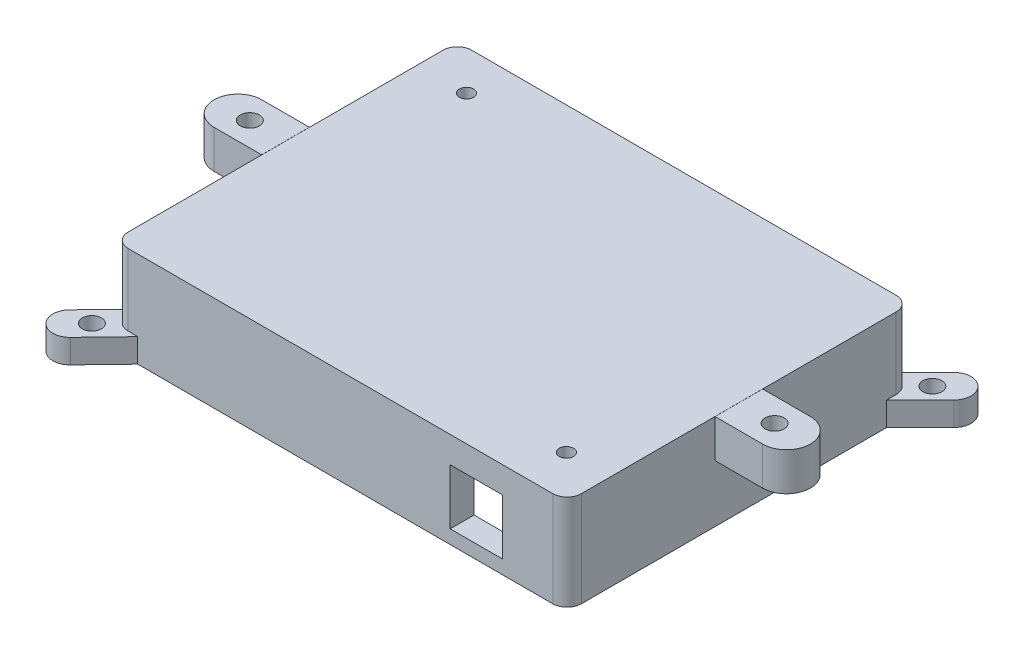
SolidWorks part; units mm, degrees
ref_plane "Plano frontal" through (0, 0, 0) normal (0, 0, 1) x (1, 0, 0)
ref_plane "Plano superior" through (0, 0, 0) normal (0, 1, 0) x (1, 0, 0)
ref_plane "Plano direito" through (0, 0, 0) normal (1, 0, 0) x (0, 0, -1)
sketch "Esboço1" plane through (0, 0, 0) normal (0, 1, 0) x (1, 0, 0)
  line L0 (9.0167, -15.2186) -> (9.0167, -20.2186) construction
  line L1 (-75.9833, 46.7814) -> (9.0167, 46.7814) construction
  line L2 (-75.9833, 46.7814) -> (-75.9833, -15.2186) construction
  line L3 (-75.9833, -15.2186) -> (9.0167, -15.2186) construction
  line L4 (9.0167, 46.7814) -> (9.0167, -15.2186) construction
  line L5 (-77.9833, 51.7814) -> (11.0167, 51.7814)
  line L6 (-80.9833, 48.7814) -> (-80.9833, -17.2186)
  line L7 (-77.9833, -20.2186) -> (11.0167, -20.2186)
  line L8 (14.0167, 48.7814) -> (14.0167, -17.2186)
  line L9 (9.0167, 46.7814) -> (9.0167, 51.7814) construction
  line L10 (-75.9833, -15.2186) -> (-80.9833, -15.2186) construction
  line L11 (9.0167, -15.2186) -> (14.0167, -15.2186) construction
  arc A0 (-80.9833, -17.2186) -> (-77.9833, -20.2186) centre (-77.9833, -17.2186) ccw
  arc A1 (11.0167, -20.2186) -> (14.0167, -17.2186) centre (11.0167, -17.2186) ccw
  arc A2 (11.0167, 51.7814) -> (14.0167, 48.7814) centre (11.0167, 48.7814) cw
  arc A3 (-77.9833, 51.7814) -> (-80.9833, 48.7814) centre (-77.9833, 48.7814) ccw
  point P14 (-80.9833, -20.2186)
  point P17 (14.0167, -20.2186)
  point P20 (14.0167, 51.7814)
  dimension "D6" = 3
  dimension "D1" = 85
  dimension "D2" = 62
  dimension "D3" = 72
  dimension "D4" = 5
  dimension "D5" = 95
extrude "Ressalto-extrusão2" add sketch "Esboço1" along normal blind 20
sketch "Esboço5" plane through (0, 20, 0) normal (0, 1, 0) x (1, 0, 0)
  line L0 (-80.1046, -19.34) -> (13.1381, 50.9027) construction
  line L1 (13.1381, -19.34) -> (-80.1046, 50.9027) construction
  line L2 (14.0167, -17.2186) -> (14.0167, -20.2186) construction
  line L3 (14.0167, -20.2186) -> (11.0167, -20.2186) construction
  line L4 (11.0167, -20.2186) -> (-77.9833, -20.2186) construction
  line L5 (-77.9833, -20.2186) -> (-80.9833, -20.2186) construction
  line L6 (-80.9833, -20.2186) -> (-80.9833, -17.2186) construction
  line L7 (-80.9833, -17.2186) -> (-80.9833, 48.7814) construction
  line L8 (-80.9833, 48.7814) -> (-80.9833, 51.7814) construction
  line L9 (-80.9833, 51.7814) -> (-77.9833, 51.7814) construction
  line L10 (-77.9833, 51.7814) -> (11.0167, 51.7814) construction
  line L11 (11.0167, 51.7814) -> (14.0167, 51.7814) construction
  line L12 (14.0167, 51.7814) -> (14.0167, 48.7814) construction
  line L13 (14.0167, 48.7814) -> (14.0167, -17.2186) construction
  line L14 (9.0167, 51.7814) -> (9.0167, -20.2186) construction
  line L15 (-75.9833, 51.7814) -> (-75.9833, -20.2186) construction
  line L16 (-80.9833, -15.2186) -> (14.0167, -15.2186) construction
  line L17 (-80.9833, 46.7814) -> (14.0167, 46.7814) construction
  line L18 (-75.9833, -15.2186) -> (-75.9833, 46.7814)
  line L19 (-75.9833, 46.7814) -> (9.0167, 46.7814)
  line L20 (9.0167, 46.7814) -> (9.0167, -15.2186)
  line L21 (9.0167, -15.2186) -> (-75.9833, -15.2186)
  arc A0 (-80.9833, -17.2186) -> (-77.9833, -20.2186) centre (-77.9833, -17.2186) ccw construction
  arc A1 (14.0167, 48.7814) -> (11.0167, 51.7814) centre (11.0167, 48.7814) ccw construction
  arc A2 (11.0167, -20.2186) -> (14.0167, -17.2186) centre (11.0167, -17.2186) ccw construction
  arc A3 (-77.9833, 51.7814) -> (-80.9833, 48.7814) centre (-77.9833, 48.7814) ccw construction
  dimension "D1" = 5
  dimension "D2" = 5
  dimension "D3" = 5
  dimension "D4" = 5
extrude "Corte-extrusão1" cut sketch "Esboço5" along normal blind 15 from surface at -20 starting at face at (-33.4833, 0, -15.7814)
sketch "Esboço6" plane through (0, 0, 20.2186) normal (0, 0, 1) x (1, 0, 0)
  line L0 (-77.9833, 0) -> (11.0167, 0) construction
  line L1 (0.5167, 2.86) -> (-10.4833, 2.86)
  line L2 (0.5167, 2.86) -> (0.5167, 14.49)
  line L3 (0.5167, 14.49) -> (-10.4833, 14.49)
  line L4 (-10.4833, 2.86) -> (-10.4833, 14.49)
  line L5 (11.0167, 20) -> (11.0167, 0) construction
  dimension "D1" = 11
  dimension "D2" = 11.63
  dimension "D3" = 2.86
  dimension "D4" = 10.5
extrude "Corte-extrusão2" cut sketch "Esboço6" against normal up to next
sketch "Esboço7" plane through (0, 20, 0) normal (0, 1, 0) x (1, 0, 0)
  line L0 (-33.4833, 51.7814) -> (-33.4833, -20.2186) construction
  line L1 (11.0167, 51.7814) -> (-77.9833, 51.7814) construction
  line L2 (-77.9833, -20.2186) -> (11.0167, -20.2186) construction
  line L3 (14.0167, 15.7814) -> (-80.9833, 15.7814) construction
  line L4 (14.0167, -17.2186) -> (14.0167, 48.7814) construction
  line L5 (-80.9833, 48.7814) -> (-80.9833, -17.2186) construction
  line L7 (-43.0633, 51.7814) -> (-23.9033, 51.7814)
  line L14 (-80.1046, 50.9027) -> (13.1381, -19.34) construction
  line L15 (-80.1046, -19.34) -> (13.1381, 50.9027) construction
  line L20 (-90.9833, 10.7814) -> (-90.9833, 20.7814) construction
  line L22 (29.0167, 15.7814) -> (14.0167, 15.7814) construction
  line L23 (-81.006, 52.1765) -> (14.0167, 52.1765) construction
  line L24 (-81.006, 52.1765) -> (-81.006, -19.8235) construction
  line L25 (-81.006, -19.8235) -> (14.0167, -19.8235) construction
  line L26 (14.0167, 52.1765) -> (14.0167, -19.8235) construction
  line L30 (-95.9833, 15.7814) -> (-80.9833, 15.7814) construction
  line L31 (-90.9833, 20.7814) -> (-81.006, 20.7814)
  line L32 (-90.9833, 10.7814) -> (-81.006, 10.7814)
  line L33 (-81.006, 10.7814) -> (-81.006, 20.7814)
  line L34 (24.0167, 10.7814) -> (24.0167, 20.7814) construction
  line L38 (14.0395, 10.7814) -> (14.0395, 20.7814)
  line L39 (24.0167, 10.7814) -> (14.0395, 10.7814)
  line L40 (24.0167, 20.7814) -> (14.0395, 20.7814)
  arc A4 (-77.9833, 51.7814) -> (-80.9833, 48.7814) centre (-77.9833, 48.7814) ccw construction
  arc A5 (11.0167, -20.2186) -> (14.0167, -17.2186) centre (11.0167, -17.2186) ccw construction
  arc A6 (-80.9833, -17.2186) -> (-77.9833, -20.2186) centre (-77.9833, -17.2186) ccw construction
  arc A7 (14.0167, 48.7814) -> (11.0167, 51.7814) centre (11.0167, 48.7814) ccw construction
  arc A10 (-90.9833, 10.7814) -> (-90.9833, 20.7814) centre (-90.9833, 15.7814) cw
  circle A16 centre (-88.4833, 15.7814) radius 2
  circle A17 centre (21.5167, 15.7814) radius 2
  arc A18 (24.0167, 10.7814) -> (24.0167, 20.7814) centre (24.0167, 15.7814) ccw
  dimension "D4" = 10
  dimension "D1" = 15
  dimension "D2" = 7.5
sketch "Esboço8" plane through (0, 0, 0) normal (0, -1, 0) x (1, 0, 0)
  line L0 (9.0167, -51.7814) -> (14.0167, -46.7814)
  line L1 (11.5167, -49.2814) -> (21.0878, -58.8524) construction
  line L2 (-75.9833, -46.7814) -> (9.0167, 15.2186) construction
  line L3 (9.0167, -46.7814) -> (9.0167, -51.7814) construction
  line L4 (11.0167, -51.7814) -> (-77.9833, -51.7814) construction
  line L5 (-33.4833, 15.2186) -> (-33.4833, -46.7814) construction
  line L6 (-75.9833, 15.2186) -> (9.0167, 15.2186) construction
  line L7 (9.0167, -51.7814) -> (16.0878, -58.8524)
  line L8 (21.0878, -53.8524) -> (16.0878, -58.8524) construction
  line L9 (9.0167, -46.7814) -> (14.0167, -46.7814) construction
  line L10 (14.0167, 17.2186) -> (14.0167, -48.7814) construction
  line L11 (14.0167, -46.7814) -> (21.0878, -53.8524)
  line L12 (9.0167, -46.7814) -> (-75.9833, -46.7814) construction
  line L13 (-75.9833, -15.7814) -> (9.0167, -15.7814) construction
  line L14 (-75.9833, -46.7814) -> (-75.9833, 15.2186) construction
  line L15 (9.0167, 15.2186) -> (9.0167, -46.7814) construction
  line L23 (-75.9833, 20.2186) -> (-81.0747, 15.3135)
  line L24 (-78.4833, 17.7186) -> (-87.9197, 27.5133) construction
  line L25 (-75.9833, 15.2186) -> (-75.9833, 20.2186) construction
  line L26 (-88.0128, 22.5151) -> (-82.9214, 27.4202) construction
  line L27 (-75.9833, 15.2186) -> (-81.0747, 15.3135) construction
  line L28 (-75.9833, 20.2186) -> (-82.9214, 27.4202)
  line L29 (-81.0747, 15.3135) -> (-88.0128, 22.5151)
  arc A0 (16.0878, -58.8524) -> (21.0878, -53.8524) centre (18.5878, -56.3524) ccw
  circle A1 centre (16.3023, -54.0669) radius 2
  arc A4 (-82.9214, 27.4202) -> (-88.0128, 22.5151) centre (-85.4671, 24.9676) ccw
  circle A5 centre (-83.2015, 22.616) radius 2
  dimension "D1" = 10
extrude "Ressalto-extrusão5" add sketch "Esboço8" against normal blind 5
extrude "Ressalto-extrusão6" add sketch "Esboço7" against normal blind 8 separate body contours A10 L32 L33 L31 A16 | L39 A18 L40 L38 A17
sketch "Esboço9" plane through (0, 15, 0) normal (0, -1, 0) x (1, 0, 0)
  line L0 (-75.9833, -46.7814) -> (-75.9833, 15.2186) construction
  line L1 (9.0167, -46.7814) -> (-75.9833, -46.7814) construction
  line L2 (-75.9833, 15.2186) -> (9.0167, 15.2186) construction
  line L3 (9.0167, 15.2186) -> (9.0167, -46.7814) construction
  circle A0 centre (-70.7333, -43.4414) radius 1.5
  circle A1 centre (4.9567, 11.2986) radius 1.5
  dimension "D1" = 5.25
  dimension "D5" = 3
  dimension "D6" = 3
  dimension "D2" = 3.34
  dimension "D3" = 3.92
  dimension "D4" = 4.06
extrude "Corte-extrusão3" cut sketch "Esboço9" against normal through all
